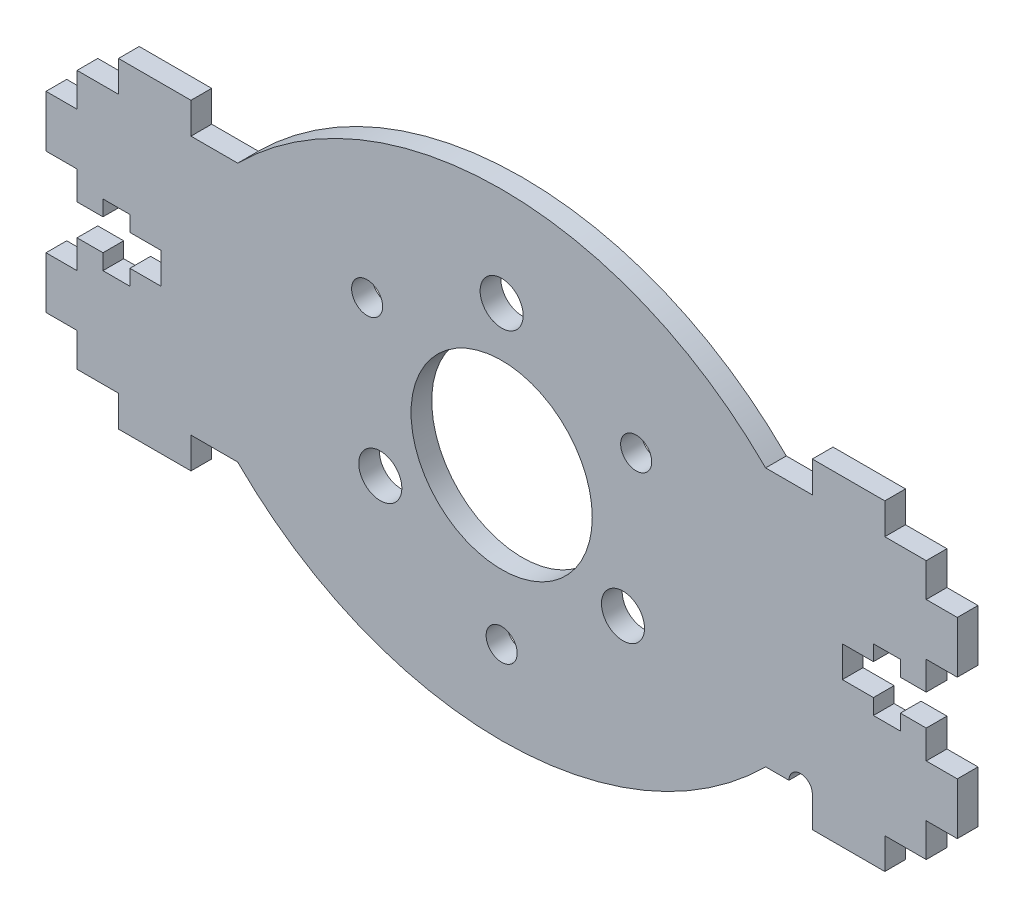
SolidWorks part; units mm, degrees
ref_plane "前视基准面" through (0, 0, 0) normal (0, 0, 1) x (1, 0, 0)
ref_plane "上视基准面" through (0, 0, 0) normal (0, 1, 0) x (1, 0, 0)
ref_plane "右视基准面" through (0, 0, 0) normal (1, 0, 0) x (0, 0, -1)
sketch "草图1" plane through (0, 0, 0) normal (0, 0, 1) x (1, 0, 0)
  line L144 (0, 0) -> (0, 8.301) construction
  line L269 (25.489, -12.5) -> (30, -12.5) construction
  line L270 (25.489, 12.5) -> (30, 12.5)
  line L275 (37, -15.5) -> (30, -15.5)
  line L286 (30, -12.5) -> (30, -15.5)
  line L287 (37, -15.5) -> (37, -12.5)
  line L288 (37, -12.5) -> (41, -12.5)
  line L291 (37, 12.5) -> (41, 12.5)
  line L292 (37, 15.5) -> (37, 12.5)
  line L293 (30, 12.5) -> (30, 15.5)
  line L304 (37, 15.5) -> (30, 15.5)
  line L359 (41, -4.25) -> (44, -4.25)
  line L360 (44, -4.25) -> (44, -9.25)
  line L361 (44, -9.25) -> (41, -9.25)
  line L362 (41, -9.25) -> (41, -12.5)
  line L363 (41, 9.25) -> (41, 12.5)
  line L364 (44, 9.25) -> (41, 9.25)
  line L365 (44, 4.25) -> (44, 9.25)
  line L366 (41, 4.25) -> (44, 4.25)
  line L389 (0, 0) -> (-15.9367, 9.2011) construction
  line L390 (0, 0) -> (40.2747, 0) construction
  line L391 (30, 12.5) -> (30, 0) construction
  line L392 (25.489, 0) -> (25.489, -12.5) construction
  line L393 (-25.489, 0) -> (-25.489, -12.5) construction
  line L394 (-30, 12.5) -> (-30, 0) construction
  line L395 (-41, 4.25) -> (-44, 4.25)
  line L396 (-44, 4.25) -> (-44, 9.25)
  line L397 (-44, 9.25) -> (-41, 9.25)
  line L398 (-41, 9.25) -> (-41, 12.5)
  line L399 (-41, -9.25) -> (-41, -12.5)
  line L400 (-44, -9.25) -> (-41, -9.25)
  line L401 (-44, -4.25) -> (-44, -9.25)
  line L402 (-41, -4.25) -> (-44, -4.25)
  line L403 (-37, 15.5) -> (-30, 15.5)
  line L404 (-30, 12.5) -> (-30, 15.5)
  line L405 (-37, 15.5) -> (-37, 12.5)
  line L406 (-37, 12.5) -> (-41, 12.5)
  line L407 (-37, -12.5) -> (-41, -12.5)
  line L408 (-37, -15.5) -> (-37, -12.5)
  line L409 (-30, -12.5) -> (-30, -15.5)
  line L410 (-37, -15.5) -> (-30, -15.5)
  line L411 (-25.489, 12.5) -> (-30, 12.5)
  line L412 (-25.489, -12.5) -> (-30, -12.5)
  line L415 (-38.5, -1.5) -> (-38.5, -3)
  line L416 (-32.9, 1.5) -> (-32.9, -1.5)
  line L417 (-38.5, 1.5) -> (-38.5, 3)
  line L418 (-41, 1.5) -> (-38.5, 1.5)
  line L419 (-38.5, -3) -> (-35.9, -3)
  line L420 (-35.9, -3) -> (-35.9, -1.5)
  line L421 (-35.9, -1.5) -> (-32.9, -1.5)
  line L422 (-35.9, 1.5) -> (-32.9, 1.5)
  line L423 (-35.9, 3) -> (-35.9, 1.5)
  line L424 (-38.5, 3) -> (-35.9, 3)
  line L425 (-38.5, -1.5) -> (-41, -1.5)
  line L426 (-41, 0) -> (-39.3727, 0) construction
  line L427 (-38.5, 1.5) -> (-41, 1.5)
  line L428 (-38.5, -3) -> (-35.9, -3)
  line L429 (-35.9, -3) -> (-35.9, -1.5)
  line L430 (-35.9, -1.5) -> (-32.9, -1.5)
  line L431 (-35.9, 1.5) -> (-32.9, 1.5)
  line L432 (-35.9, 3) -> (-35.9, 1.5)
  line L433 (-38.5, 3) -> (-35.9, 3)
  line L434 (-41, -1.5) -> (-38.5, -1.5)
  line L435 (-38.5, -1.5) -> (-38.5, -3)
  line L436 (-38.5, 1.5) -> (-38.5, 3)
  line L437 (-41, 4.25) -> (-41, 1.5)
  line L438 (-41, -1.5) -> (-41, -4.25)
  line L439 (38.5, -1.5) -> (41, -1.5)
  line L440 (41, 1.5) -> (38.5, 1.5)
  line L441 (38.5, 1.5) -> (38.5, 3)
  line L442 (38.5, -1.5) -> (38.5, -3)
  line L443 (38.5, 3) -> (35.9, 3)
  line L444 (35.9, 3) -> (35.9, 1.5)
  line L445 (35.9, 1.5) -> (32.9, 1.5)
  line L446 (35.9, -1.5) -> (32.9, -1.5)
  line L447 (35.9, -3) -> (35.9, -1.5)
  line L448 (38.5, -3) -> (35.9, -3)
  line L449 (38.5, 3) -> (35.9, 3)
  line L450 (35.9, 3) -> (35.9, 1.5)
  line L451 (35.9, 1.5) -> (32.9, 1.5)
  line L452 (35.9, -1.5) -> (32.9, -1.5)
  line L453 (35.9, -3) -> (35.9, -1.5)
  line L454 (38.5, -3) -> (35.9, -3)
  line L455 (38.5, 1.5) -> (38.5, 3)
  line L456 (32.9, 1.5) -> (32.9, -1.5)
  line L457 (38.5, -1.5) -> (38.5, -3)
  line L458 (41, 4.25) -> (41, 1.5)
  line L459 (41, -1.5) -> (41, -4.25)
  line L460 (27.7445, -12.5) -> (25.489, -12.5)
  circle A13 centre (0, 0) radius 15 construction
  circle A14 centre (0, 0) radius 13.53 construction
  circle A21 centre (0, 13.53) radius 2.08
  circle A22 centre (11.7173, -6.765) radius 2.08
  circle A23 centre (-11.7173, -6.765) radius 2.08
  circle A24 centre (0, 0) radius 8.75
  circle A25 centre (-12.9904, 7.5) radius 1.5
  circle A26 centre (12.9904, 7.5) radius 1.5
  circle A27 centre (0, -15) radius 1.5
  arc A28 (-25.489, 12.5) -> (25.489, 12.5) centre (0, -12.989) cw
  arc A29 (-25.489, -12.5) -> (25.489, -12.5) centre (0, 12.989) ccw
  arc A30 (30, -12.5) -> (27.7445, -12.5) centre (28.8722, -12.5) ccw
  dimension "D1" = 3
  dimension "D3" = 3
  dimension "D4" = 12.5
  dimension "D2" = 60
  dimension "D5" = 12.5
extrude "凸台-拉伸2" add sketch "草图1" along normal blind 2
sketch "草图7" plane through (41, 0, 0) normal (1, 0, 0) x (0, 0, -1)
  line L0 (0, -9.25) -> (0.1, -9.25)
  line L1 (0.1, -9.25) -> (0.1, -4.4)
  line L2 (0.1, -4.4) -> (-2.1, -4.4)
sketch "草图8" plane through (41, 0, 0) normal (1, 0, 0) x (0, 0, -1)
  line L0 (-1, 1.5) -> (-1, -1.5)
  line L1 (-2, 1.5) -> (0, 1.5) construction
  line L2 (-2, -1.5) -> (0, -1.5) construction
  circle A0 centre (-1, 0) radius 1.5
sketch "草图9" plane through (-41, 0, 0) normal (-1, 0, 0) x (0, 0, 1)
  line L0 (1, 1.5) -> (1, -1.5)
  line L1 (2, 1.5) -> (0, 1.5) construction
  line L2 (2, -1.5) -> (0, -1.5) construction
  circle A0 centre (1, 0) radius 1.5
